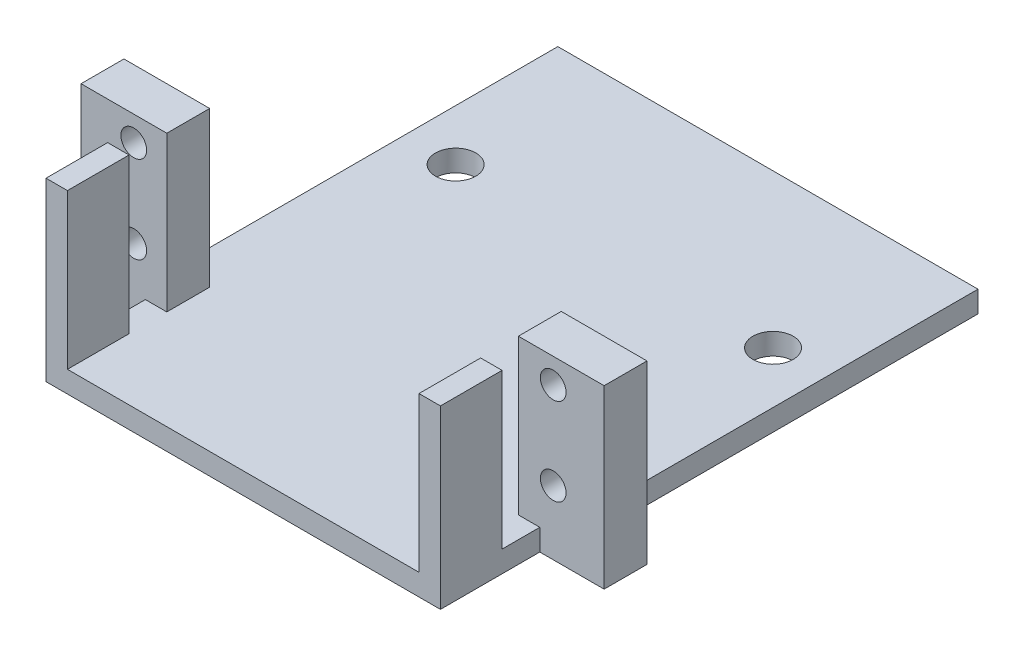
SolidWorks part; units mm, degrees
ref_plane "Front Plane" through (0, 0, 0) normal (0, 0, 1) x (1, 0, 0)
ref_plane "Top Plane" through (0, 0, 0) normal (0, 1, 0) x (1, 0, 0)
ref_plane "Right Plane" through (0, 0, 0) normal (1, 0, 0) x (0, 0, -1)
sketch "Sketch1" plane through (0, 0, 0) normal (0, 1, 0) x (1, 0, 0)
  line L1 (0, 0) -> (46, 0)
  line L2 (0, 0) -> (0, 36.614)
  line L3 (0, 36.614) -> (46, 36.614)
  line L4 (46, 0) -> (46, 36.614)
  dimension "D1" = 46
extrude "Boss-Extrude1" add sketch "Sketch1" along normal blind 2.5
sketch "Sketch2" plane through (0, 2.5, 0) normal (0, 1, 0) x (1, 0, 0)
  line L1 (0, 36.614) -> (2.5, 36.614)
  line L2 (0, 36.614) -> (0, 11.588)
  line L3 (0, 11.588) -> (2.5, 11.588)
  line L4 (2.5, 36.614) -> (2.5, 11.588)
  line L5 (0, 0) -> (2.5, 0)
  line L6 (0, 0) -> (0, 7.188)
  line L7 (0, 7.188) -> (2.5, 7.188)
  line L8 (2.5, 0) -> (2.5, 7.188)
  line L9 (46, 0) -> (43.5, 0)
  line L10 (46, 0) -> (46, 7.188)
  line L11 (46, 7.188) -> (43.5, 7.188)
  line L12 (43.5, 0) -> (43.5, 7.188)
  line L13 (46, 36.614) -> (43.5, 36.614)
  line L14 (46, 36.614) -> (46, 11.588)
  line L15 (46, 11.588) -> (43.5, 11.588)
  line L16 (43.5, 36.614) -> (43.5, 11.588)
  point P20 (44.75, 7.188)
  dimension "D1" = 2.5
  dimension "D2" = 2.5
  dimension "D3" = 2.5
  dimension "D4" = 2.5
  dimension "D5" = 7.188
  dimension "D6" = 4.4
  dimension "D7" = 7.188
  dimension "D8" = 4.4
extrude "Boss-Extrude2" add sketch "Sketch2" along normal blind 20.8351
sketch "Sketch4" plane through (0, 0, -11.588) normal (0, 0, 1) x (1, 0, 0)
  line L0 (2.5, 23.3351) -> (2.5, 2.5) construction
  line L1 (2.5, 20.5529) -> (-7.5, 20.5529)
  line L2 (2.5, 20.5529) -> (2.5, 0)
  line L3 (2.5, 0) -> (-7.5, 0)
  line L4 (-7.5, 20.5529) -> (-7.5, 0)
  line L5 (43.5, 23.3351) -> (43.5, 2.5) construction
  line L6 (43.5, 20.5529) -> (53.5, 20.5529)
  line L7 (43.5, 20.5529) -> (43.5, 0)
  line L8 (43.5, 0) -> (53.5, 0)
  line L9 (53.5, 20.5529) -> (53.5, 0)
  dimension "D1" = 10
  dimension "D2" = 10
extrude "Boss-Extrude8" add sketch "Sketch4" against normal blind 5
sketch "Sketch5" plane through (0, 0, 0) normal (-1, 0, 0) x (0, 0, 1)
  line L1 (-36.614, 23.3351) -> (-16.588, 23.3351)
  line L2 (-36.614, 23.3351) -> (-36.614, 0)
  line L3 (-36.614, 0) -> (-16.588, 0)
  line L4 (-16.588, 23.3351) -> (-16.588, 0)
extrude "Cut-Extrude1" cut sketch "Sketch5" against normal blind 100
sketch "Sketch6" plane through (0, 0, -16.588) normal (0, 0, -1) x (-1, 0, 0)
  line L0 (7.5, 0) -> (-53.5, 0) construction
  line L1 (-47.5, 2.5) -> (1.5, 2.5)
  line L2 (-47.5, 2.5) -> (-47.5, 0)
  line L3 (-47.5, 0) -> (1.5, 0)
  line L4 (1.5, 2.5) -> (1.5, 0)
  line L5 (-53.5, 0) -> (-53.5, 20.5529) construction
  line L6 (7.5, 20.5529) -> (7.5, 0) construction
  dimension "D1" = 2.5
  dimension "D2" = 6
  dimension "D3" = 6
extrude "Boss-Extrude9" add sketch "Sketch6" along normal blind 44.6018
sketch "Sketch7" plane through (0, 2.5, 0) normal (0, 1, 0) x (1, 0, 0)
  circle A0 centre (4.4582, 43.3138) radius 2.35
  circle A1 centre (41.4728, 43.3138) radius 2.35
  dimension "D1" = 4.7
  dimension "D2" = 4.7
extrude "Cut-Extrude2" cut sketch "Sketch7" against normal blind 57
sketch "Sketch8" plane through (0, 0, 0) normal (0, 0, 1) x (1, 0, 0)
sketch "Sketch9" plane through (0, 0, 0) normal (-1, 0, 0) x (0, 0, 1)
  line L1 (0, 23.3351) -> (-16.588, 23.3351)
  line L2 (0, 23.3351) -> (0, 20.5529)
  line L3 (0, 20.5529) -> (-16.588, 20.5529)
  line L4 (-16.588, 23.3351) -> (-16.588, 20.5529)
extrude "Cut-Extrude3" cut sketch "Sketch9" against normal blind 47
sketch "Sketch10" plane through (0, 0, -11.588) normal (0, 0, 1) x (1, 0, 0)
  circle A0 centre (-1.3535, 17.6577) radius 1.5
  circle A1 centre (-1.3535, 7.4923) radius 1.5
  circle A2 centre (47.5607, 17.6577) radius 1.5
  circle A3 centre (47.5607, 7.4923) radius 1.5
  dimension "D1" = 3
  dimension "D2" = 3
  dimension "D3" = 3
  dimension "D5" = 3
extrude "Cut-Extrude4" cut sketch "Sketch10" against normal blind 10
